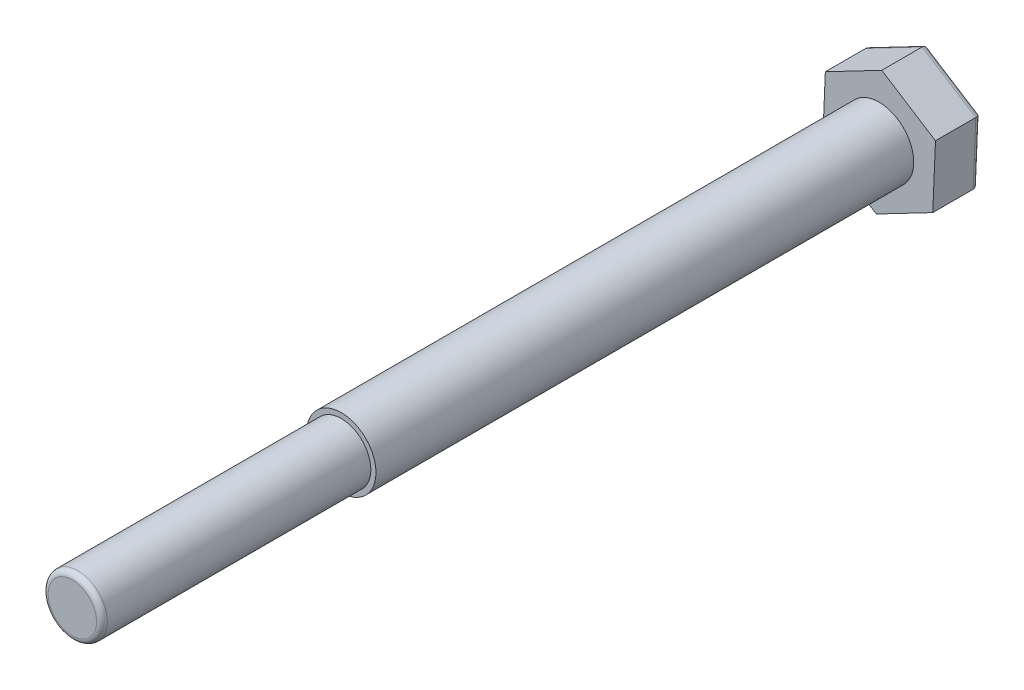
SolidWorks part; units mm, degrees
ref_plane "前视" through (0, 0, 0) normal (0, 0, 1) x (1, 0, 0)
ref_plane "上视" through (0, 0, 0) normal (0, 1, 0) x (1, 0, 0)
ref_plane "右视" through (0, 0, 0) normal (1, 0, 0) x (0, 0, -1)
sketch "草图1" plane through (0, 0, 0) normal (0, 0, 1) x (1, 0, 0)
  line L1 (20.9842, 10.9543) -> (1.0054, 23.65)
  line L2 (1.0054, 23.65) -> (-19.9788, 12.6957)
  line L3 (-19.9788, 12.6957) -> (-20.9842, -10.9543)
  line L4 (-20.9842, -10.9543) -> (-1.0054, -23.65)
  line L5 (-1.0054, -23.65) -> (19.9788, -12.6957)
  line L6 (19.9788, -12.6957) -> (20.9842, 10.9543)
  circle A0 centre (0, 0) radius 20.5 construction
  dimension "D1" = 47.3
  dimension "D2" = 41
extrude "基体-拉伸" add sketch "草图1" along normal blind 17
sketch "草图2" plane through (0, 0, 17) normal (0, 0, 1) x (1, 0, 0)
  circle A0 centre (0, 0) radius 12.9
  dimension "D1" = 25.8
extrude "凸台-拉伸1" add sketch "草图2" along normal blind 200
fillet "圆角3" radius 2 6 edges at (9.4867, -18.1729, 0) (-10.9948, -17.3021, 0) (-20.4815, 0.8707, 0) (-9.4867, 18.1729, 0) (10.9948, 17.3021, 0) (20.4815, -0.8707, 0)
sketch "草图3" plane through (0, 0, 217) normal (0, 0, 1) x (1, 0, 0)
  circle A0 centre (0, 0) radius 11
  dimension "D1" = 22
extrude "凸台-拉伸2" add sketch "草图3" along normal blind 100
fillet "圆角4" radius 2 1 edges at (11, 0, 317)
